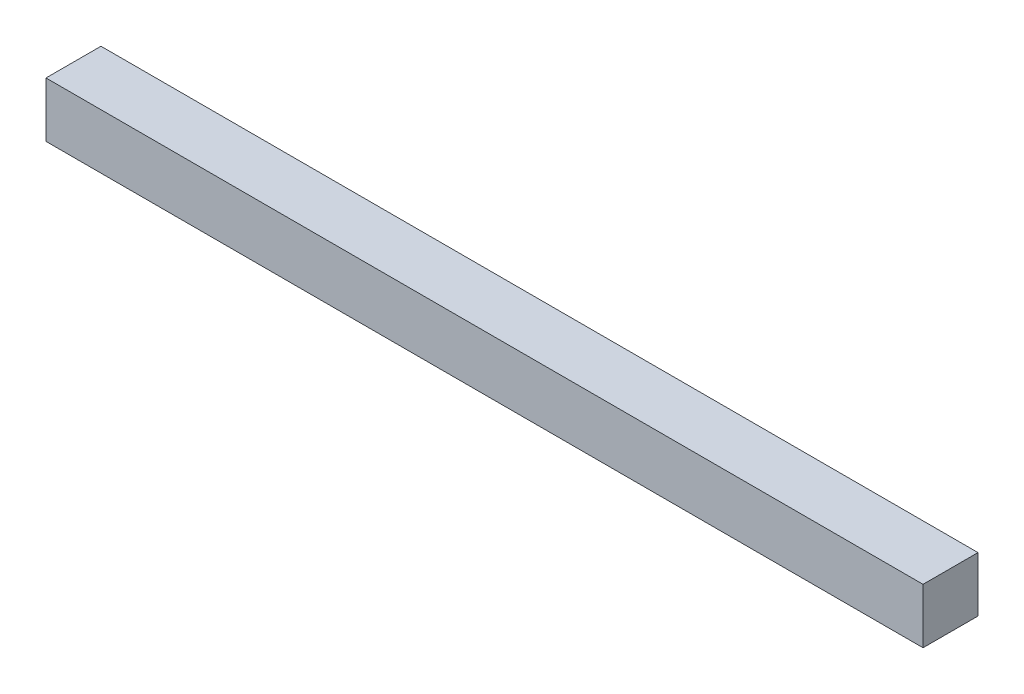
SolidWorks part; units mm, degrees
ref_plane "Alzado" through (0, 0, 0) normal (0, 0, 1) x (1, 0, 0)
ref_plane "Planta" through (0, 0, 0) normal (0, 1, 0) x (1, 0, 0)
ref_plane "Vista lateral" through (0, 0, 0) normal (1, 0, 0) x (0, 0, -1)
sketch "Croquis1" plane through (0, 0, 0) normal (0, 0, 1) x (1, 0, 0)
  line L0 (0, 0) -> (0, -18)
  line L1 (0, 0) -> (287.21, 0)
  line L2 (0, -18) -> (287.21, -18)
  line L3 (287.21, -18) -> (287.21, 0)
extrude "Saliente-Extruir1" add sketch "Croquis1" against normal blind 18
